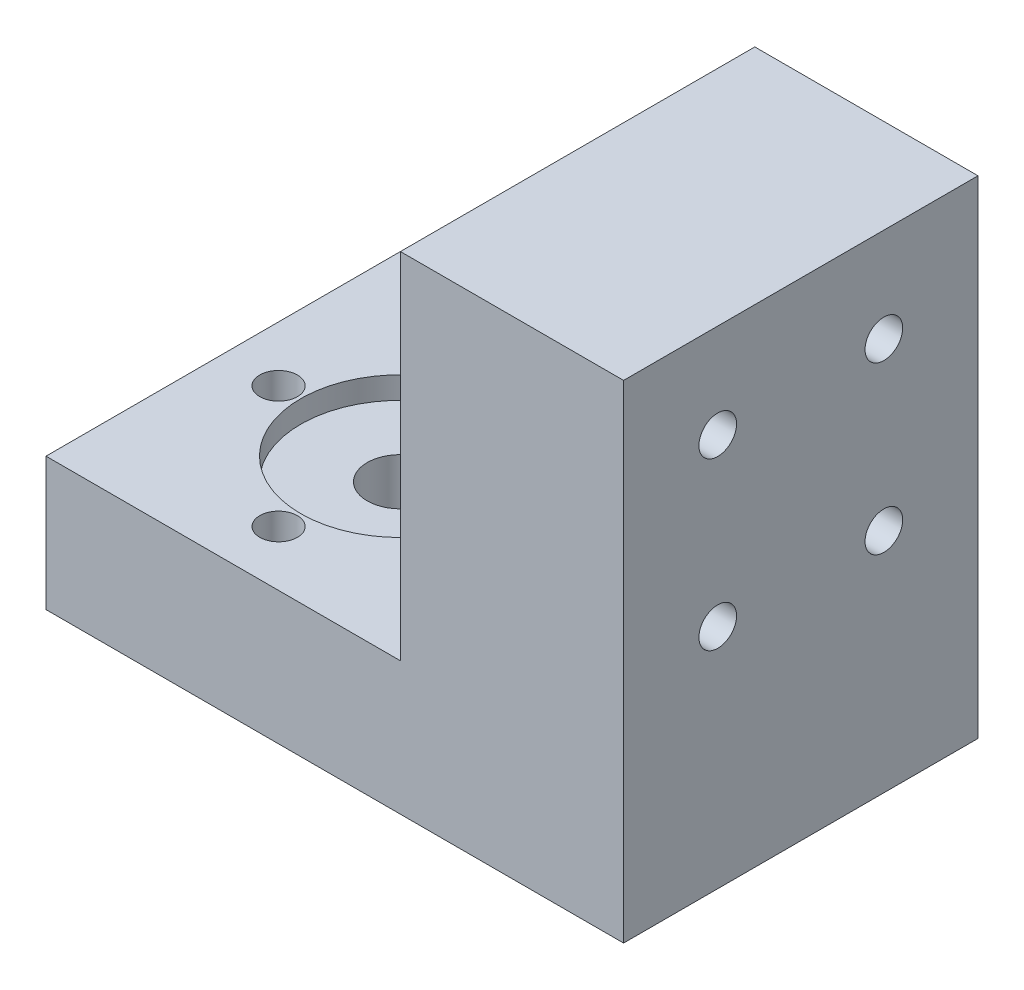
SolidWorks part; units mm, degrees
material "ABS"
ref_plane "Front Plane" through (0, 0, 0) normal (0, 0, 1) x (1, 0, 0)
ref_plane "Top Plane" through (0, 0, 0) normal (0, 1, 0) x (1, 0, 0)
ref_plane "Right Plane" through (0, 0, 0) normal (1, 0, 0) x (0, 0, -1)
sketch "Sketch1" plane through (0, 0, 0) normal (0, 1, 0) x (1, 0, 0)
  line L1 (0, 0) -> (32, 0)
  line L2 (0, 0) -> (0, 32)
  line L3 (0, 32) -> (32, 32)
  line L4 (32, 0) -> (32, 32)
  dimension "D1" = 32
  dimension "D2" = 32
extrude "Boss-Extrude1" add sketch "Sketch1" along normal blind 12 contours L1 L4 L3 L2
sketch "Sketch3" plane through (0, 12, 0) normal (0, 1, 0) x (1, 0, 0)
  line L0 (0, 16) -> (32, 16)
  line L1 (0, 0) -> (0, 32) construction
  line L2 (32, 0) -> (32, 32) construction
  circle A0 centre (16, 16) radius 9
  dimension "D1" = 18
extrude "Cut-Extrude1" cut sketch "Sketch3" against normal blind 2 contours A0
sketch "Sketch5" plane through (0, 10, 0) normal (0, 1, 0) x (1, 0, 0)
  circle A0 centre (16, 16) radius 3
  dimension "D1" = 6
extrude "Cut-Extrude2" cut sketch "Sketch5" against normal through all contours A0
sketch "Sketch6" plane through (0, 12, 0) normal (0, 1, 0) x (1, 0, 0)
  circle A0 centre (16, 16) radius 11
  circle A1 centre (16, 27) radius 1.7
  circle A2 centre (5, 16) radius 1.7
  circle A3 centre (16, 5) radius 1.7
  circle A4 centre (27, 16) radius 1.7
  dimension "D1" = 22
  dimension "D2" = 3.4
  dimension "D3" = 3.4
  dimension "D4" = 3.4
  dimension "D5" = 3.4
extrude "Cut-Extrude3" cut sketch "Sketch6" against normal through all contours A1 | A4 | A3 | A2
sketch "Sketch7" plane through (32, 0, 0) normal (1, 0, 0) x (0, 0, -1)
  line L1 (0, 0) -> (32, 0)
  line L2 (0, 0) -> (0, 44)
  line L3 (0, 44) -> (32, 44)
  line L4 (32, 0) -> (32, 44)
  dimension "D2" = 32
  dimension "D1" = 44
extrude "Boss-Extrude3" add sketch "Sketch7" along normal blind 20.1522
sketch "Sketch8" plane through (32, 0, 0) normal (-1, 0, 0) x (0, 0, 1)
  line L0 (-16, 44) -> (-16, 12) construction
  line L3 (-32, 44) -> (0, 44) construction
  line L4 (0, 12) -> (-32, 12) construction
  line L6 (-23.5, 20.5) -> (-8.5, 20.5)
  line L7 (-23.5, 20.5) -> (-23.5, 35.5)
  line L8 (-23.5, 35.5) -> (-8.5, 35.5)
  line L9 (-8.5, 20.5) -> (-8.5, 35.5)
  line L10 (-23.5, 20.5) -> (-8.5, 35.5) construction
  line L11 (-23.5, 35.5) -> (-8.5, 20.5) construction
  circle A0 centre (-23.5, 35.5) radius 1.7
  circle A1 centre (-8.5, 35.5) radius 1.7
  circle A2 centre (-8.5, 20.5) radius 1.7
  circle A3 centre (-23.5, 20.5) radius 1.7
  point P6 (-16, 28)
  point P15 (0, 0)
  point P16 (0, 0)
  dimension "D3" = 3.4
  dimension "D4" = 3.4
  dimension "D5" = 3.4
  dimension "D6" = 3.4
  dimension "D1" = 15
  dimension "D2" = 15
extrude "Cut-Extrude4" cut sketch "Sketch8" against normal through all contours A0 | A1 | A2 | A3
equation "\"P\"= 300"
equation "\"Delta\"= .3"
equation "\"SF\"= 3"
equation "\"E\" = 2000"
equation "\"stress_yield\"= 30"
equation "\"b\"= 32"
equation "\"L_1\"= 32"
equation "\"M_1\"= \"P\" * 18"
equation "\"stress_max\"= \"stress_yield\" / \"SF\""
equation "\"D1@Sketch1\"=\"L_1\""
equation "\"D2@Sketch1\"=\"L_1\""
equation "\"H_1\" = ( ( \"M_1\" * ( \"L_1\" * 6 ) ) / ( \"Delta\" * \"E\" ) ) ^ ( 1 / 3 )"
equation "\"H_2\" = ( ( \"M_2\" * ( \"L_2\" * 6 ) ) / ( \"Delta\" * \"E\" ) ) ^ ( 1 / 3 )"
equation "\"L_2\"= \"L_1\" + \"H_1\""
equation "\"M_2\"= \"P\" * ( 18 + \"L_2\" )"
equation "\"D_1\" = 6.0"
equation "\"D_2\"= 18"
equation "\"D_3\"= 22"
equation "\"m3\"= 3.4"
equation "\"D1@Boss-Extrude1\"=\"H_1\""
equation "\"D1@Sketch3\"=\"D_2\""
equation "\"Depth\"= 2"
equation "\"D1@Cut-Extrude1\"= \"Depth\""
equation "\"D1@Sketch5\"=\"D_1\""
equation "\"D1@Sketch6\"=\"D_3\""
equation "\"D2@Sketch6\"=\"m3\""
equation "\"D3@Sketch6\"=\"m3\""
equation "\"D4@Sketch6\"=\"m3\""
equation "\"D5@Sketch6\"=\"m3\""
equation "\"D1@Sketch7\"=\"L_2\""
equation "\"D2@Sketch7\"=\"L_1\""
equation "\"D1@Boss-Extrude3\"= \"H_2\""
equation "\"Width\" = 15"
equation "\"D1@Sketch8\"=\"Width\""
equation "\"D2@Sketch8\"=\"Width\""
equation "\"D3@Sketch8\"=\"m3\""
equation "\"D4@Sketch8\"=\"m3\""
equation "\"D5@Sketch8\"=\"m3\""
equation "\"D6@Sketch8\"=\"m3\""
